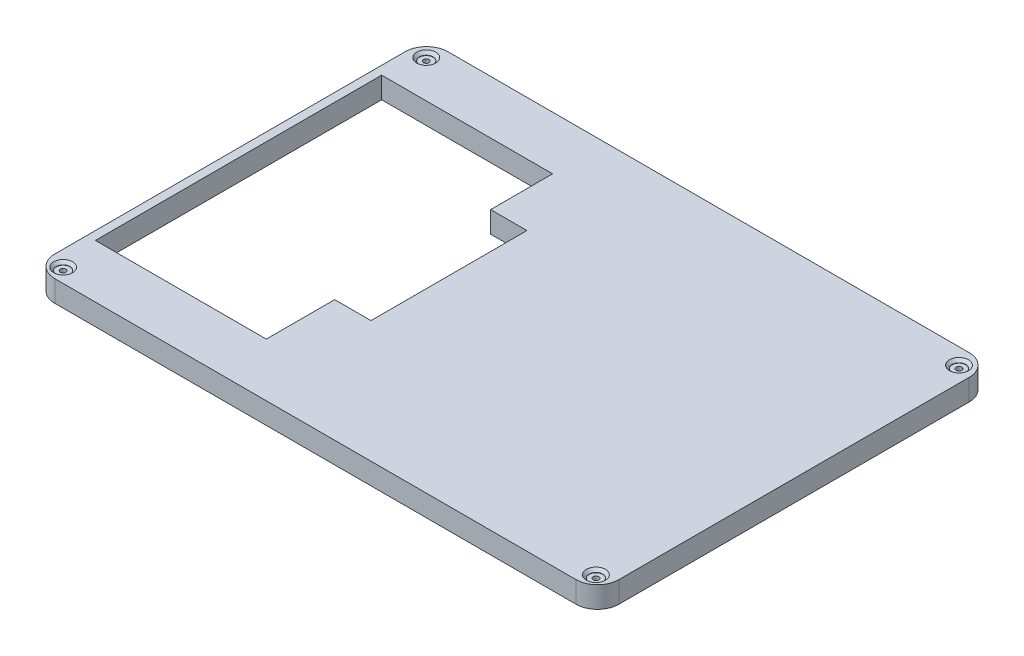
SolidWorks part; units mm, degrees
ref_plane "Front Plane" through (0, 0, 0) normal (0, 0, 1) x (1, 0, 0)
ref_plane "Top Plane" through (0, 0, 0) normal (0, 1, 0) x (1, 0, 0)
ref_plane "Right Plane" through (0, 0, 0) normal (1, 0, 0) x (0, 0, -1)
sketch "Sketch2" plane through (0, 0, 0) normal (0, 1, 0) x (1, 0, 0)
  line L0 (-55, 0) -> (55, 0) construction
  line L1 (-61, -46) -> (61, -46)
  line L2 (-66, -41) -> (-66, 41)
  line L3 (-61, 46) -> (61, 46)
  line L4 (66, -41) -> (66, 41)
  line L5 (-66, -46) -> (66, 46) construction
  line L6 (-66, 46) -> (66, -46) construction
  line L7 (-64, -33.5) -> (-24, -33.5)
  line L8 (-64, -33.5) -> (-64, 33.5)
  line L9 (-64, 33.5) -> (-24, 33.5)
  line L10 (-24, -33.5) -> (-24, -17.5)
  line L11 (-64, -33.5) -> (-24, 33.5) construction
  line L12 (-64, 33.5) -> (-24, -33.5) construction
  line L13 (-24, 19) -> (-24, 33.5)
  line L14 (-24, 19) -> (-15.5, 19)
  line L16 (-24, -17.5) -> (-15.5, -17.5)
  line L17 (-15.5, 19) -> (-15.5, -17.5)
  arc A0 (-61, -46) -> (-66, -41) centre (-61, -41) cw
  arc A1 (61, -46) -> (66, -41) centre (61, -41) ccw
  arc A2 (61, 46) -> (66, 41) centre (61, 41) cw
  arc A3 (-66, 41) -> (-61, 46) centre (-61, 41) cw
  point P0 (0, 0)
  point P18 (-44, 0)
  dimension "D3" = 5
  dimension "D1" = 92
  dimension "D2" = 132
  dimension "D4" = 67
  dimension "D5" = 40
  dimension "D6" = 2
  dimension "D7" = 14.5
  dimension "D8" = 16
  dimension "D9" = 8.5
extrude "Boss-Extrude1" add sketch "Sketch2" along normal blind 5
hole_wizard "CBORE for #00 Binding Head Machine Screw1" positions "3DSketch1" profile "Sketch5" counterbore size "#00" standard "ANSI Inch"
sketch3d "3DSketch1"
  point P0 (-62.3404, 5, -42.2683)
  point P2 (62.3404, 5, -42.2683)
  point P4 (-62.3404, 5, 42.7012)
  point P6 (62.3404, 5, 42.7012)
  point P9 (-62.3404, 5, -42.2683)
  point P10 (-62.3404, 5, -42.2683)
  point P11 (-62.3404, 5, 42.7012)
  point P12 (62.3404, 5, 42.7012)
  point P13 (62.3404, 5, -42.2683)
sketch "Sketch5" plane through (-62.3404, 5, -42.2683) normal (1, 0, 0) x (0, 0, 1)
  line L0 (0, 0) -> (0, 5.3968)
  line L1 (0, 5.3968) -> (0.6604, 5)
  line L2 (0.6604, 5) -> (0.6604, 0.7112)
  line L3 (0.6604, 0.7112) -> (1.5875, 0.7112)
  line L5 (1.5875, 0.7112) -> (1.5875, 0.635)
  line L6 (1.5875, 0.635) -> (2.2225, 0)
  line L7 (2.2225, 0) -> (0, 0)
  line L8 (-1.5875, 0.635) -> (-2.2225, 0) construction
  line L10 (0, 5.3968) -> (-0.6604, 5) construction
  line L11 (0, -6.35) -> (0, 107.95) construction
  dimension "Hole Dia." = 1.3208
  dimension "Hole Depth" = 5
  dimension "C'Bore Dia." = 3.175
  dimension "C'Bore Depth" = 0.7112
  dimension "Near C'Sink Dia." = 4.445
  dimension "Near C'Sink Angle" = 90
  dimension "Drill Angle" = 118
